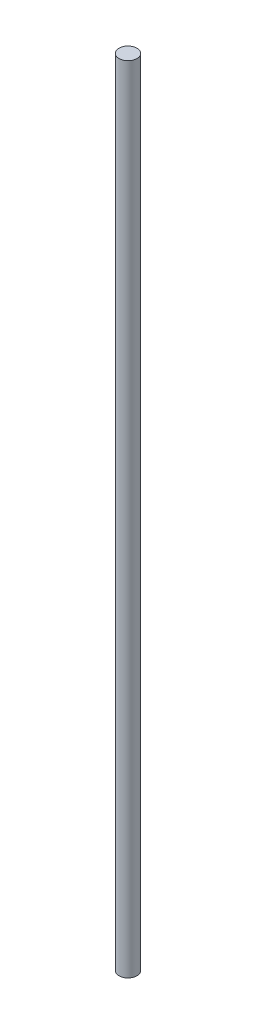
SolidWorks part; units mm, degrees
material "ABS"
ref_plane "Alzado" through (0, 0, 0) normal (0, 0, 1) x (1, 0, 0)
ref_plane "Planta" through (0, 0, 0) normal (0, 1, 0) x (1, 0, 0)
ref_plane "Vista lateral" through (0, 0, 0) normal (1, 0, 0) x (0, 0, -1)
sketch "Croquis1" plane through (0, 0, 0) normal (0, 1, 0) x (1, 0, 0)
  circle A0 centre (0, 0) radius 4.25
  dimension "D1" = 8.5
extrude "Saliente-Extruir1" add sketch "Croquis1" along normal blind 375
